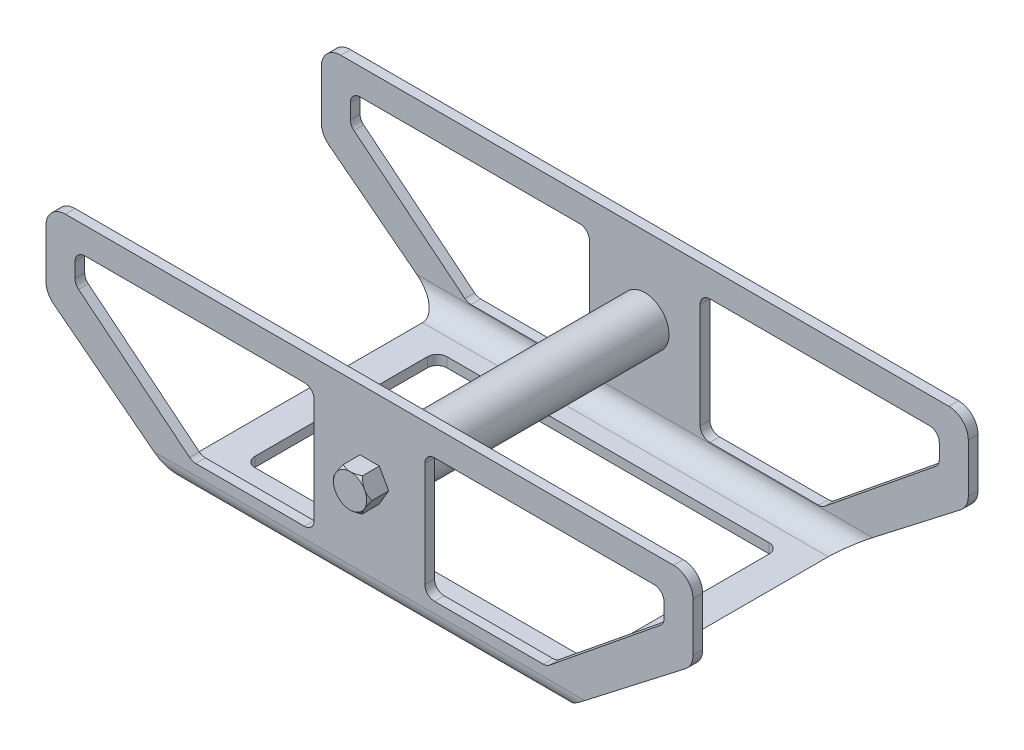
SolidWorks part; units mm, degrees
ref_plane "Front Plane" through (0, 0, 0) normal (0, 0, 1) x (1, 0, 0)
ref_plane "Top Plane" through (0, 0, 0) normal (0, 1, 0) x (1, 0, 0)
ref_plane "Right Plane" through (0, 0, 0) normal (1, 0, 0) x (0, 0, -1)
sketch "Sketch1" plane through (0, 0, 0) normal (0, 0, 1) x (1, 0, 0)
  line L0 (0, 0) -> (0, -255.6224) construction
  line L1 (-333.43, 0) -> (333.43, 0)
  line L2 (333.43, 0) -> (333.43, -80.23)
  line L3 (333.43, -80.23) -> (196.11, -186.5035)
  line L4 (196.11, -186.5035) -> (-196.11, -186.5035)
  line L5 (-333.43, -80.23) -> (-196.11, -186.5035)
  line L6 (-333.43, 0) -> (-333.43, -80.23)
  point P9 (0, -186.5035)
  dimension "D1" = 333.43
  dimension "D2" = 80.23
  dimension "D3" = 173.64
  dimension "D4" = 196.11
extrude "Boss-Extrude1" add sketch "Sketch1" along normal mid plane 293.75
sketch "Sketch2" plane through (333.43, 0, 0) normal (1, 0, 0) x (0, 0, -1)
  line L0 (-146.875, -80.23) -> (146.875, -80.23) construction
  line L1 (-136.875, 16.0435) -> (136.875, 16.0435)
  line L2 (-136.875, 16.0435) -> (-136.875, -176.5035)
  line L3 (-136.875, -176.5035) -> (136.875, -176.5035)
  line L4 (136.875, 16.0435) -> (136.875, -176.5035)
  line L5 (-136.875, 16.0435) -> (136.875, -176.5035) construction
  line L6 (-136.875, -176.5035) -> (136.875, 16.0435) construction
  line L7 (-146.875, -80.23) -> (-146.875, 0) construction
  line L8 (-146.875, -186.5035) -> (146.875, -186.5035) construction
  point P0 (0, -80.23)
  dimension "D1" = 10
  dimension "D2" = 10
extrude "Cut-Extrude1" cut sketch "Sketch2" against normal through all
fillet "Fillet1" radius 20 2 edges at (0, -186.5035, 146.875) (0, -186.5035, -146.875)
fillet "Fillet2" radius 20 2 edges at (0, -176.5035, 136.875) (0, -176.5035, -136.875)
sketch "Sketch3" plane through (0, 0, 146.875) normal (0, 0, 1) x (1, 0, 0)
  circle A0 centre (0, -80.23) radius 25
  dimension "D1" = 50
extrude "Boss-Extrude2" add sketch "Sketch3" against normal up to surface (283.75 mm away) up to face at (0, -78.9112, -136.875)
sketch "Sketch4" plane through (0, 0, -146.875) normal (0, 0, -1) x (-1, 0, 0)
  line L0 (-333.43, -80.23) -> (160.8841, -80.23) construction
  line L1 (9.7329, -62.9862) -> (-10.0671, -63.1792)
  line L2 (-10.0671, -63.1792) -> (-19.8, -80.423)
  line L3 (-19.8, -80.423) -> (-9.7329, -97.4738)
  line L4 (-9.7329, -97.4738) -> (10.0671, -97.2808)
  line L5 (10.0671, -97.2808) -> (19.8, -80.037)
  line L6 (19.8, -80.037) -> (9.7329, -62.9862)
  line L7 (0, 0) -> (0, -148.7321) construction
  line L8 (-333.43, 0) -> (333.43, 0) construction
  circle A0 centre (0, -80.23) radius 17.1481 construction
  dimension "D1" = 19.8
extrude "Boss-Extrude3" add sketch "Sketch4" along normal blind 20 separate body
sketch "Sketch5" plane through (0, 0, -166.875) normal (0, 0, -1) x (-1, 0, 0)
  circle A0 centre (0, -80.23) radius 17.1481
  circle A1 centre (0, -80.23) radius 27.7866
extrude "Cut-Extrude3" cut sketch "Sketch5" against normal blind 20 draft 45
mirror "Mirror1" about plane through (0, 0, 0) normal (0, 0, 1) of bodies 106
sketch "Sketch6" plane through (0, 0, -146.875) normal (0, 0, -1) x (-1, 0, 0)
  line L0 (-303.5, -52.66) -> (-303.5, -37.26)
  line L1 (-293.5, -27.26) -> (-67, -27.26)
  line L2 (-57, -37.26) -> (-57, -145.43)
  line L3 (-67, -155.43) -> (-179.12, -155.43)
  line L4 (-185.4192, -153.1966) -> (-299.7992, -60.4266)
  line L5 (-333.43, -80.23) -> (-333.43, 0) construction
  line L6 (-333.43, 0) -> (333.43, 0) construction
  line L7 (0, 0) -> (0, -122.0255) construction
  line L8 (67, -155.43) -> (179.12, -155.43)
  line L9 (57, -37.26) -> (57, -145.43)
  line L10 (293.5, -27.26) -> (67, -27.26)
  line L11 (303.5, -52.66) -> (303.5, -37.26)
  line L12 (185.4192, -153.1966) -> (299.7992, -60.4266)
  arc A0 (-303.5, -52.66) -> (-299.7992, -60.4266) centre (-293.5, -52.66) ccw
  arc A1 (-179.12, -155.43) -> (-185.4192, -153.1966) centre (-179.12, -145.43) cw
  arc A2 (-57, -145.43) -> (-67, -155.43) centre (-67, -145.43) cw
  arc A3 (-67, -27.26) -> (-57, -37.26) centre (-67, -37.26) cw
  arc A4 (-303.5, -37.26) -> (-293.5, -27.26) centre (-293.5, -37.26) cw
  arc A5 (57, -145.43) -> (67, -155.43) centre (67, -145.43) ccw
  arc A6 (67, -27.26) -> (57, -37.26) centre (67, -37.26) ccw
  arc A7 (303.5, -37.26) -> (293.5, -27.26) centre (293.5, -37.26) ccw
  arc A8 (303.5, -52.66) -> (299.7992, -60.4266) centre (293.5, -52.66) cw
  arc A9 (179.12, -155.43) -> (185.4192, -153.1966) centre (179.12, -145.43) ccw
  dimension "D1" = 10
  dimension "D2" = 226.5
  dimension "D3" = 112.12
  dimension "D4" = 108.17
  dimension "D5" = 15.4
  dimension "D6" = 29.93
  dimension "D7" = 27.26
extrude "Cut-Extrude4" cut sketch "Sketch6" against normal through all
sketch "Sketch8" plane through (0, -186.5035, 0) normal (0, -1, 0) x (1, 0, 0)
  line L0 (-196.11, 126.875) -> (-196.11, -126.875) construction
  line L1 (-176.11, -99) -> (176.11, -99)
  line L2 (-176.11, -99) -> (-176.11, 99)
  line L3 (-176.11, 99) -> (176.11, 99)
  line L4 (176.11, -99) -> (176.11, 99)
  line L5 (-176.11, -99) -> (176.11, 99) construction
  line L6 (-176.11, 99) -> (176.11, -99) construction
  point P0 (0, 0)
  dimension "D1" = 198
  dimension "D2" = 20
extrude "Cut-Extrude5" cut sketch "Sketch8" against normal blind 20
fillet "Fillet3" radius 20 8 edges at (333.43, -80.23, 141.875) (333.43, 0, 141.875) (333.43, -80.23, -141.875) (333.43, 0, -141.875) (-333.43, -80.23, -141.875) (-333.43, 0, -141.875) (-333.43, -80.23, 141.875) (-333.43, 0, 141.875)
fillet "Fillet4" radius 10 4 edges at (-176.11, -181.5035, 99) (176.11, -181.5035, 99) (176.11, -181.5035, -99) (-176.11, -181.5035, -99)
